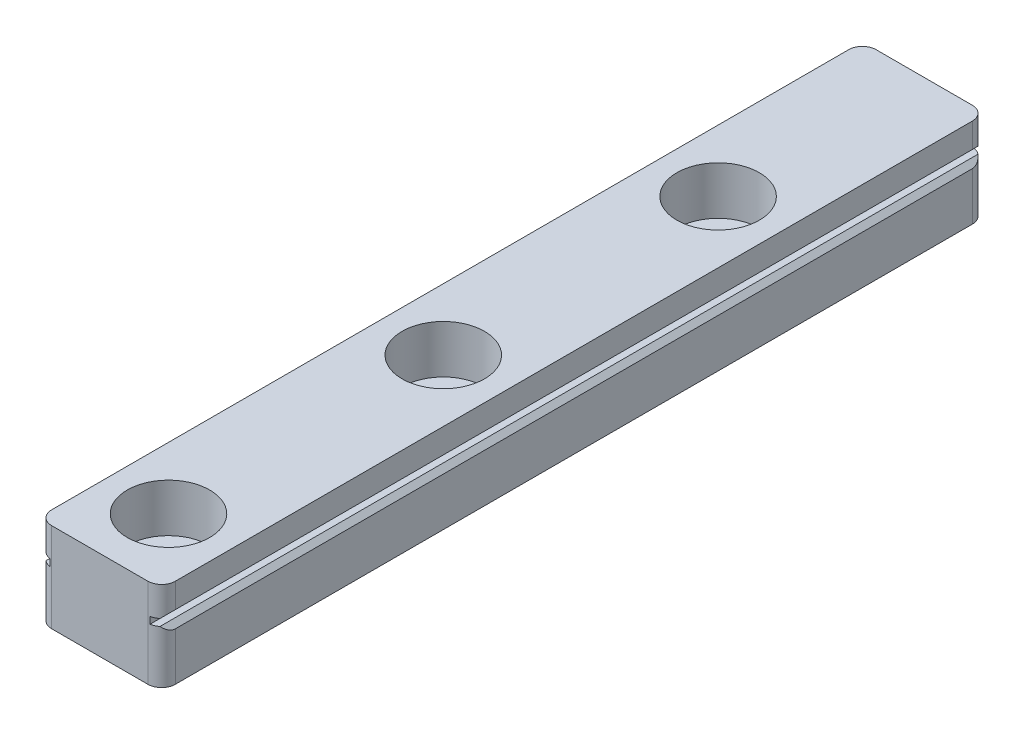
SolidWorks part; units mm, degrees
material "镀铬不锈钢"
ref_plane "前视基准面" through (0, 0, 0) normal (0, 0, 1) x (1, 0, 0)
ref_plane "上视基准面" through (0, 0, 0) normal (0, 1, 0) x (1, 0, 0)
ref_plane "右视基准面" through (0, 0, 0) normal (1, 0, 0) x (0, 0, -1)
sketch "草图2" plane through (0, 0, 0) normal (0, 0, 1) x (1, 0, 0)
  line L0 (0, 0) -> (9, 0)
  line L1 (4.5, 0) -> (4.5, 7.3268) construction
  line L2 (9, 0) -> (9, 3.5)
  line L3 (9, 3.5) -> (8.6464, 3.8536)
  line L4 (8.6464, 3.8536) -> (8.1464, 3.8536)
  line L5 (8.1464, 3.8536) -> (8.1464, 4.3536)
  line L6 (8.1464, 4.3536) -> (8.6464, 4.3536)
  line L7 (8.6464, 4.3536) -> (9, 4.7071)
  line L8 (9, 4.7071) -> (9, 6.5)
  line L9 (9, 6.5) -> (0, 6.5)
  line L10 (0, 4.7071) -> (0, 6.5)
  line L11 (0.3536, 4.3536) -> (0, 4.7071)
  line L12 (0.8536, 4.3536) -> (0.3536, 4.3536)
  line L13 (0.8536, 3.8536) -> (0.8536, 4.3536)
  line L14 (0.3536, 3.8536) -> (0.8536, 3.8536)
  line L15 (0, 3.5) -> (0.3536, 3.8536)
  line L16 (0, 0) -> (0, 3.5)
  point P14 (4.5, 6.5)
  dimension "D1" = 9
  dimension "D2" = 3.5
  dimension "D3" = 135
  dimension "D4" = 0.5
  dimension "D5" = 0.5
  dimension "D6" = 0.5
  dimension "D7" = 0.5
  dimension "D8" = 6.5
extrude "凸台-拉伸2" add sketch "草图2" against normal blind 60
sketch "草图3" plane through (0, 6.5, 0) normal (0, 1, 0) x (1, 0, 0)
  line L0 (9, 0) -> (0, 0) construction
  circle A0 centre (4.5, 5) radius 3
  circle A1 centre (4.5, 25) radius 3
  circle A2 centre (4.5, 45) radius 3
  circle A3 centre (4.5, 65) radius 3
  circle A4 centre (4.5, 85) radius 3
  circle A5 centre (4.5, 105) radius 3
  circle A6 centre (4.5, 125) radius 3
  circle A7 centre (4.5, 45) radius 3 [skipped]
  circle A8 centre (4.5, 65) radius 3 [skipped]
  circle A9 centre (4.5, 85) radius 3 [skipped]
  circle A10 centre (4.5, 105) radius 3 [skipped]
  circle A11 centre (4.5, 125) radius 3 [skipped]
  circle A16 centre (4.5, 145) radius 3
  circle A17 centre (4.5, 165) radius 3
  circle A18 centre (4.5, 185) radius 3
  circle A19 centre (4.5, 205) radius 3
  circle A20 centre (4.5, 225) radius 3
  circle A29 centre (4.5, 145) radius 3 [skipped]
  circle A30 centre (4.5, 165) radius 3 [skipped]
  circle A31 centre (4.5, 185) radius 3 [skipped]
  circle A32 centre (4.5, 205) radius 3 [skipped]
  circle A33 centre (4.5, 305) radius 3 [skipped]
  circle A34 centre (4.5, 325) radius 3 [skipped]
  circle A35 centre (4.5, 345) radius 3 [skipped]
  circle A36 centre (4.5, 365) radius 3 [skipped]
  circle A37 centre (4.5, 385) radius 3 [skipped]
  circle A38 centre (4.5, 265) radius 3 [skipped]
  circle A39 centre (4.5, 285) radius 3 [skipped]
  circle A40 centre (4.5, 245) radius 3 [skipped]
  point P2 (4.5, 0)
  dimension "D1" = 6
  dimension "D4" = 6
  dimension "D2" = 5
  dimension "D5" = 20
  dimension "D3" = 20
  dimension "D6" = 9
extrude "切除-拉伸1" cut sketch "草图3" against normal blind 3.5
sketch "草图4" plane through (0, 3, 0) normal (0, 1, 0) x (1, 0, 0)
  circle A0 centre (4.5, 5) radius 1.75
  circle A1 centre (4.5, 25) radius 1.75
  circle A2 centre (4.5, 45) radius 1.75
  circle A3 centre (4.5, 65) radius 1.75
  circle A4 centre (4.5, 85) radius 1.75
  circle A5 centre (4.5, 105) radius 1.75
  circle A6 centre (4.5, 125) radius 1.75
  circle A7 centre (4.5, 65) radius 1.75 [skipped]
  circle A8 centre (4.5, 85) radius 1.75 [skipped]
  circle A9 centre (4.5, 105) radius 1.75 [skipped]
  circle A10 centre (4.5, 125) radius 1.75 [skipped]
  circle A11 centre (4.5, 45) radius 1.75 [skipped]
  circle A12 centre (4.5, 145) radius 1.75
  circle A13 centre (4.5, 165) radius 1.75
  circle A14 centre (4.5, 185) radius 1.75
  circle A15 centre (4.5, 205) radius 1.75
  circle A16 centre (4.5, 225) radius 1.75
  circle A25 centre (4.5, 265) radius 1.75 [skipped]
  circle A26 centre (4.5, 285) radius 1.75 [skipped]
  circle A27 centre (4.5, 305) radius 1.75 [skipped]
  circle A28 centre (4.5, 325) radius 1.75 [skipped]
  circle A29 centre (4.5, 345) radius 1.75 [skipped]
  circle A30 centre (4.5, 365) radius 1.75 [skipped]
  circle A31 centre (4.5, 385) radius 1.75 [skipped]
  circle A32 centre (4.5, 245) radius 1.75 [skipped]
  dimension "D1" = 3.5
  dimension "D3" = 3.5
  dimension "D2" = 7
  dimension "D4" = 18
extrude "切除-拉伸2" cut sketch "草图4" against normal up to surface (3 mm away) up to face at (4.5, 0, -30)
fillet "圆角1" radius 1 4 edges at (9, 1.75, -60) (0, 1.75, -60) (9, 1.75, 0) (0, 1.75, 0)
